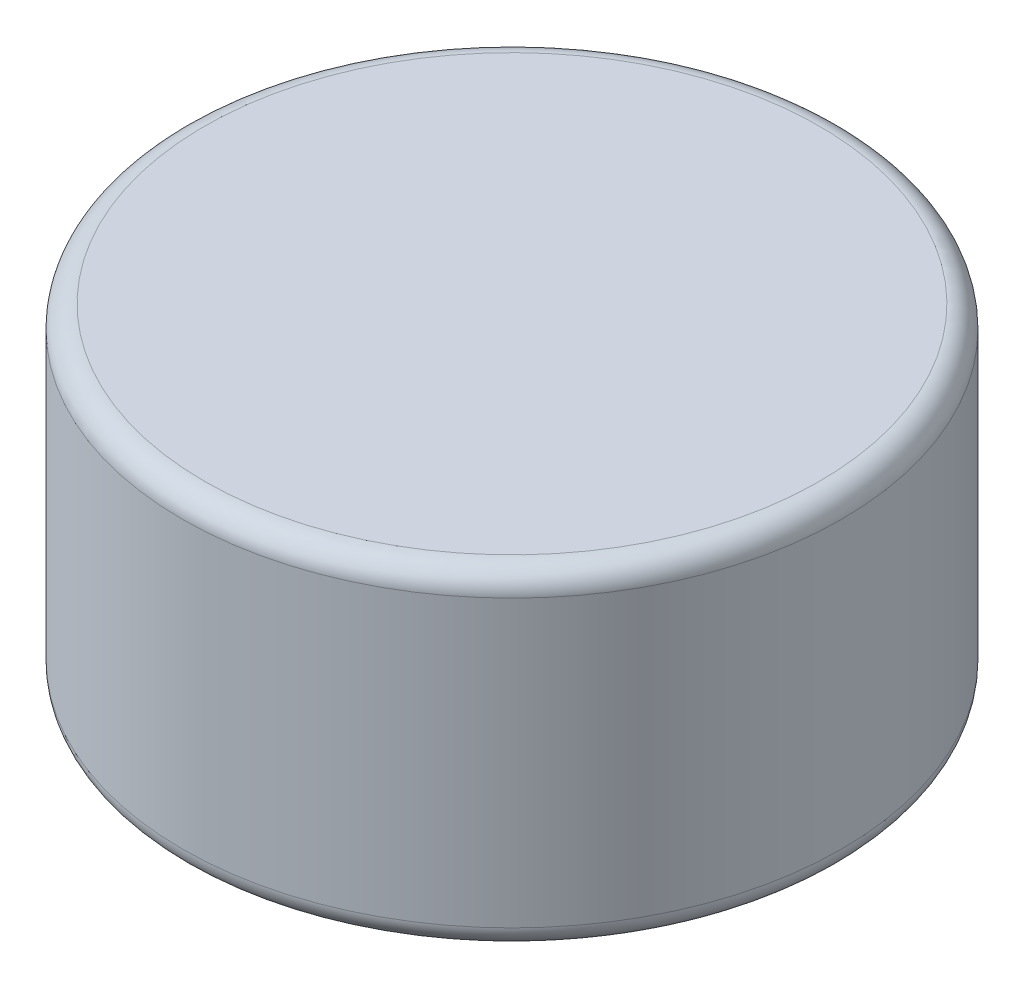
SolidWorks part; units mm, degrees
ref_plane "前视基准面" through (0, 0, 0) normal (0, 0, 1) x (1, 0, 0)
ref_plane "上视基准面" through (0, 0, 0) normal (0, 1, 0) x (1, 0, 0)
ref_plane "右视基准面" through (0, 0, 0) normal (1, 0, 0) x (0, 0, -1)
other "Configuration Table"
sketch "草图1" plane through (0, 0, 0) normal (0, 1, 0) x (1, 0, 0)
  circle A0 centre (0, 0) radius 3
  dimension "D1" = 6
extrude "凸台-拉伸1" add sketch "草图1" along normal blind 3
fillet "圆角1" radius 0.2 2 edges at (0, 0, 3) (0, 3, 3)
